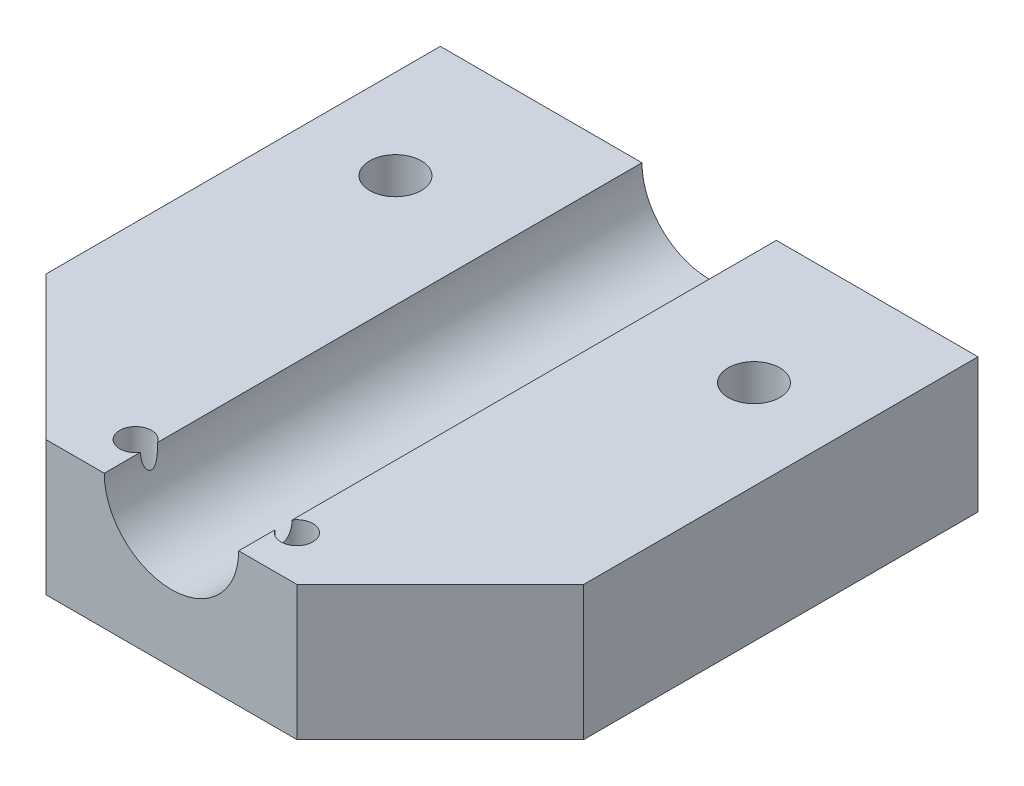
SolidWorks part; units mm, degrees
material "ABS PC"
ref_plane "Front Plane" through (0, 0, 0) normal (0, 0, 1) x (1, 0, 0)
ref_plane "Top Plane" through (0, 0, 0) normal (0, 1, 0) x (1, 0, 0)
ref_plane "Right Plane" through (0, 0, 0) normal (1, 0, 0) x (0, 0, -1)
sketch "Sketch1" plane through (0, 0, 0) normal (0, 1, 0) x (1, 0, 0)
  line L1 (-19.05, -19.05) -> (19.05, -19.05)
  line L2 (-19.05, -19.05) -> (-19.05, 19.05)
  line L3 (-19.05, 19.05) -> (19.05, 19.05)
  line L4 (19.05, -19.05) -> (19.05, 19.05)
  line L5 (-19.05, -19.05) -> (19.05, 19.05) construction
  line L6 (-19.05, 19.05) -> (19.05, -19.05) construction
  point P0 (0, 0)
  dimension "D1" = 38.1
  dimension "D2" = 38.1
extrude "Boss-Extrude1" add sketch "Sketch1" along normal blind 9.525
sketch "Sketch4" plane through (0, 0, 19.05) normal (0, 0, 1) x (1, 0, 0)
  line L0 (-19.05, 9.525) -> (19.05, 9.525) construction
  circle A0 centre (0, 9.525) radius 4.7625
  dimension "D1" = 9.525
extrude "Cut-Extrude1" cut sketch "Sketch4" against normal through all
hole_wizard "MotorHoles" positions "Sketch3" profile "Sketch2" tap size "#4-40" standard "ANSI Inch" end condition through all
sketch "Sketch3" plane through (0, 0, 0) normal (0, -1, 0) x (-1, 0, 0)
  line L0 (19.05, -19.05) -> (-19.05, -19.05) construction
  line L2 (0, 0) -> (0, -31.1437) construction
  point P0 (-5.715, -15.875)
  point P2 (5.715, -15.875)
  dimension "D1" = 3.175
  dimension "D2" = 11.43
sketch "Sketch2" plane through (5.715, 0, 15.875) normal (1, 0, 0) x (0, 0, -1)
  line L0 (0, 0) -> (0, 9.525)
  line L1 (0, 9.525) -> (1.1303, 9.525)
  line L2 (1.1303, 9.525) -> (1.1303, 0)
  line L5 (1.1303, 0) -> (0, 0)
  line L11 (0, -6.35) -> (0, 107.95) construction
  dimension "Thru Tap Drill Dia." = 2.2606
  dimension "Thru Tap Drill Depth" = 9.525
cosmetic thread "Hole Thread1" parameters "D2"=2.8448
cosmetic thread "Hole Thread2" parameters "D2"=2.8448
hole_wizard "CBORE for #6 Socket Head Cap Screw1" positions "Sketch6" profile "Sketch5" counterbore size "#6" standard "ANSI Inch" end condition through all
sketch "Sketch6" plane through (0, 0, 0) normal (0, -1, 0) x (-1, 0, 0)
  line L0 (0, 0) -> (0, 20.3228) construction
  line L2 (-19.05, 19.05) -> (19.05, 19.05) construction
  point P0 (-12.7, 9.525)
  point P2 (12.7, 9.525)
  dimension "D1" = 25.4
  dimension "D2" = 9.525
sketch "Sketch5" plane through (12.7, 0, -9.525) normal (1, 0, 0) x (0, 0, -1)
  line L0 (0, 0) -> (0, 9.525)
  line L1 (0, 9.525) -> (1.8288, 9.525)
  line L3 (1.8288, 9.525) -> (1.8288, 3.5052)
  line L4 (3.5725, 3.5052) -> (1.8288, 3.5052)
  line L5 (3.5725, 3.5052) -> (3.5725, 0.635)
  line L6 (3.5725, 0.635) -> (4.2075, 0)
  line L7 (4.2075, 0) -> (0, 0)
  line L8 (-3.5725, 0.635) -> (-4.2075, 0) construction
  line L11 (0, -6.35) -> (0, 107.95) construction
  dimension "Thru Hole Dia." = 3.6576
  dimension "Thru Hole Depth" = 9.525
  dimension "C'Bore Dia." = 7.145
  dimension "C'Bore Depth" = 3.5052
  dimension "Near C'Sink Dia." = 8.415
  dimension "Near C'Sink Angle" = 90
chamfer "Chamfer1" distance 10.16 angle 45 2 edges at (19.05, 4.7625, 19.05) (-19.05, 4.7625, 19.05)
